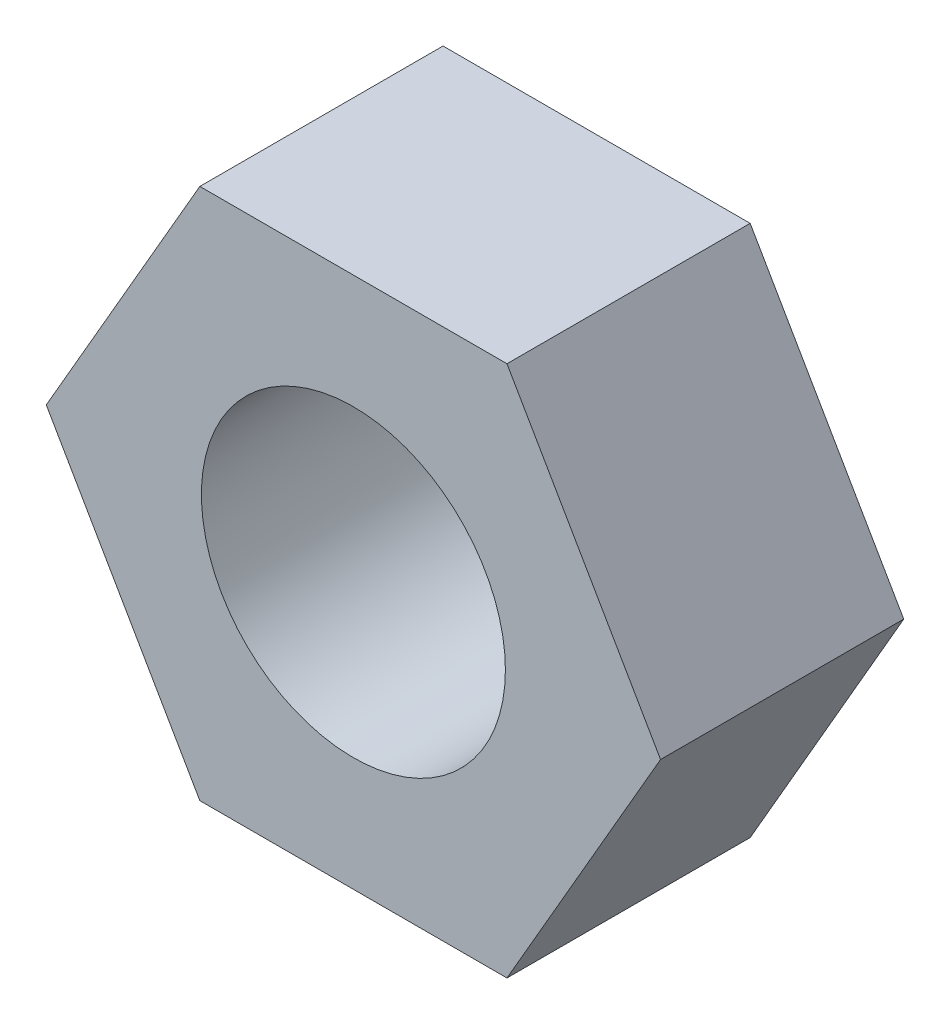
SolidWorks part; units mm, degrees
material "尼龙 101"
ref_plane "前视基准面" through (0, 0, 0) normal (0, 0, 1) x (1, 0, 0)
ref_plane "上视基准面" through (0, 0, 0) normal (0, 1, 0) x (1, 0, 0)
ref_plane "右视基准面" through (0, 0, 0) normal (1, 0, 0) x (0, 0, -1)
sketch "草图1" plane through (0, 0, 0) normal (0, 0, 1) x (1, 0, 0)
  line L1 (4.0415, 0) -> (2.0207, 3.5)
  line L2 (2.0207, 3.5) -> (-2.0207, 3.5)
  line L3 (-2.0207, 3.5) -> (-4.0415, 0)
  line L4 (-4.0415, 0) -> (-2.0207, -3.5)
  line L5 (-2.0207, -3.5) -> (2.0207, -3.5)
  line L6 (2.0207, -3.5) -> (4.0415, 0)
  circle A0 centre (0, 0) radius 3.5 construction
  circle A1 centre (0, 0) radius 2
  dimension "对边距离" = 7
  dimension "螺纹直径" = 4
extrude "凸台-拉伸1" add sketch "草图1" along normal mid plane 3.2
